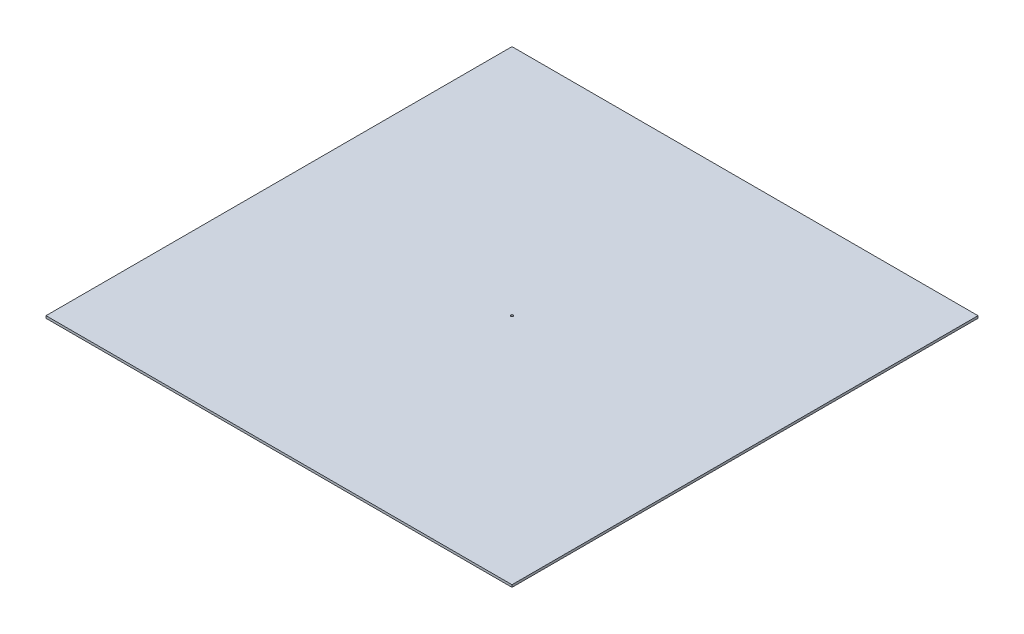
SolidWorks part; units mm, degrees
ref_plane "前基準面" through (0, 0, 0) normal (0, 0, 1) x (1, 0, 0)
ref_plane "上基準面" through (0, 0, 0) normal (0, 1, 0) x (1, 0, 0)
ref_plane "右基準面" through (0, 0, 0) normal (1, 0, 0) x (0, 0, -1)
sketch "草圖1" plane through (0, 0, 0) normal (0, 1, 0) x (1, 0, 0)
  line L1 (-1000, 1000) -> (1000, 1000)
  line L2 (-1000, 1000) -> (-1000, -1000)
  line L3 (-1000, -1000) -> (1000, -1000)
  line L4 (1000, 1000) -> (1000, -1000)
  line L5 (-1000, 1000) -> (1000, -1000) construction
  line L6 (-1000, -1000) -> (1000, 1000) construction
  point P0 (0, 0)
  dimension "D1" = 2000
  dimension "D2" = 2000
extrude "填料-伸長1" add sketch "草圖1" along normal blind 10
sketch "草圖2" plane through (0, 10, 0) normal (0, 1, 0) x (1, 0, 0)
  circle A0 centre (0, 0) radius 5
  dimension "D1" = 10
extrude "除料-伸長1" cut sketch "草圖2" against normal blind 10
